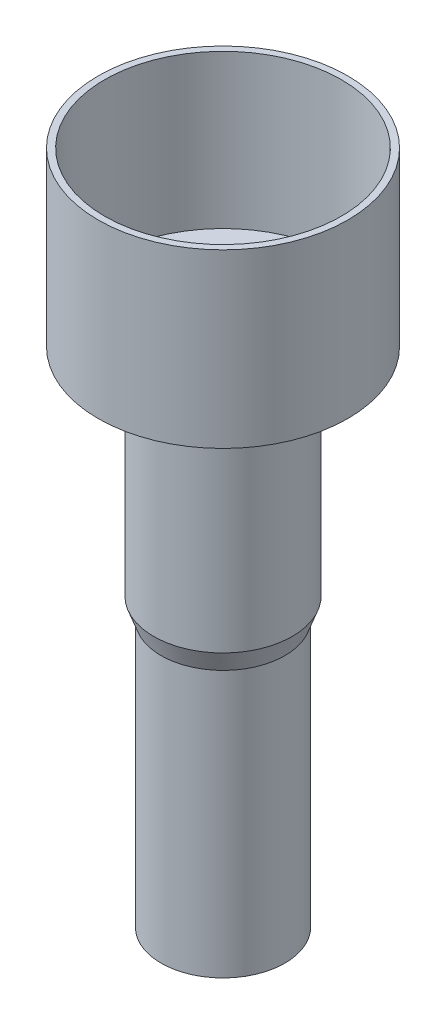
SolidWorks part; units mm, degrees
ref_plane "Front Plane" through (0, 0, 0) normal (0, 0, 1) x (1, 0, 0)
ref_plane "Top Plane" through (0, 0, 0) normal (0, 1, 0) x (1, 0, 0)
ref_plane "Right Plane" through (0, 0, 0) normal (1, 0, 0) x (0, 0, -1)
sketch "Sketch1" plane through (0, 0, 0) normal (0, 0, 1) x (1, 0, 0)
  line L0 (0, 0) -> (0, 36.5) construction
  line L1 (0, 36.5) -> (-6.4, 36.5) construction
  line L2 (-6.4, 36.5) -> (-6.4, 28.2)
  line L3 (-6.4, 28.2) -> (-2.1, 28.2)
  line L4 (-2.1, 28.2) -> (-2.1, 24)
  line L5 (-1.5, 23) -> (-2.15, 23)
  line L6 (-1.5, 24) -> (-1.5, 23)
  line L7 (-2.15, 23) -> (-2.15, 0)
  line L8 (-6.4, 36.5) -> (-6.75, 36.5)
  line L9 (-2.15, 0) -> (0, 0)
  line L10 (-2.1, 24) -> (-1.5, 24)
  line L11 (-6.75, 36.5) -> (-6.75, 27.2)
  line L12 (-6.75, 27.2) -> (-3.75, 27.2)
  line L13 (-3.75, 27.2) -> (-3.75, 15.5)
  line L14 (-3.75, 15.5) -> (-3.35, 14.401)
  line L15 (-3.35, 14.401) -> (-3.35, 0)
  line L16 (-3.35, 0) -> (-2.15, 0)
  dimension "D1" = 8.3
  dimension "D2" = 36.5
  dimension "D3" = 4.2
  dimension "D4" = 2.1
  dimension "D5" = 1
  dimension "D6" = 1.5
  dimension "D7" = 2.15
  dimension "D8" = 6.4
  dimension "D9" = 6.75
  dimension "D10" = 1
  dimension "D11" = 11.7
  dimension "D12" = 3.35
  dimension "D13" = 20
  dimension "D14" = 3.75
revolve "Revolve1" add sketch "Sketch1" angle 360 about L0
